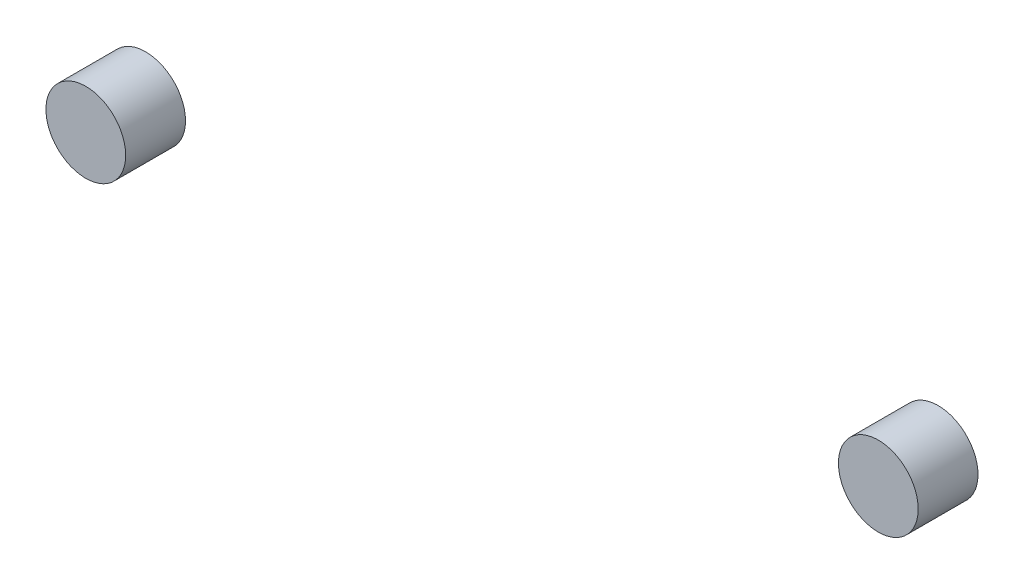
SolidWorks part; units mm, degrees
ref_plane "前视基准面" through (0, 0, 0) normal (0, 0, 1) x (1, 0, 0)
ref_plane "上视基准面" through (0, 0, 0) normal (0, 1, 0) x (1, 0, 0)
ref_plane "右视基准面" through (0, 0, 0) normal (1, 0, 0) x (0, 0, -1)
sketch "草图1" plane through (0, 0, 0) normal (0, 0, 1) x (1, 0, 0)
  line L0 (0, 0) -> (24.9219, -31.2874)
  line L1 (24.9219, -31.2874) -> (-14.0815, -76.8805)
  line L2 (-14.0815, -76.8805) -> (-10.9662, -80.7915)
  line L3 (24.9219, -31.2874) -> (28.0371, -35.1983)
  line L8 (31.7796, 9.6182) -> (29.5188, -25.3087)
  line L9 (41.3863, -27.0866) -> (7.9653, -5.1085)
  line L10 (0, 0) -> (19.8725, 2.2549)
  line L11 (7.9653, -5.1085) -> (31.7796, 9.6182)
  line L12 (-10.9662, -80.7915) -> (13.9557, -112.0788)
  line L13 (28.0371, -35.1983) -> (-10.9662, -80.7915)
  line L14 (-10.9662, -80.7915) -> (41.3863, -27.0866)
  line L15 (41.3863, -27.0866) -> (29.5188, -25.3087)
  line L16 (29.5188, -25.3087) -> (28.0371, -35.1983)
  circle A0 centre (19.8725, 2.2549) radius 14
  circle A1 centre (19.8725, 2.2549) radius 1
  circle A2 centre (0, 0) radius 1
  dimension "D6" = 28
  dimension "D1" = 40
  dimension "D2" = 40
  dimension "D4" = 5
  dimension "D5" = 60
  dimension "D7" = 20
  dimension "D8" = 35
  dimension "D9" = 40
  dimension "D10" = 75
  dimension "D11" = 12
  dimension "D12" = 10
extrude "凸台-拉伸1" add sketch "草图1" along normal blind 1.5 contours A2 | A1
